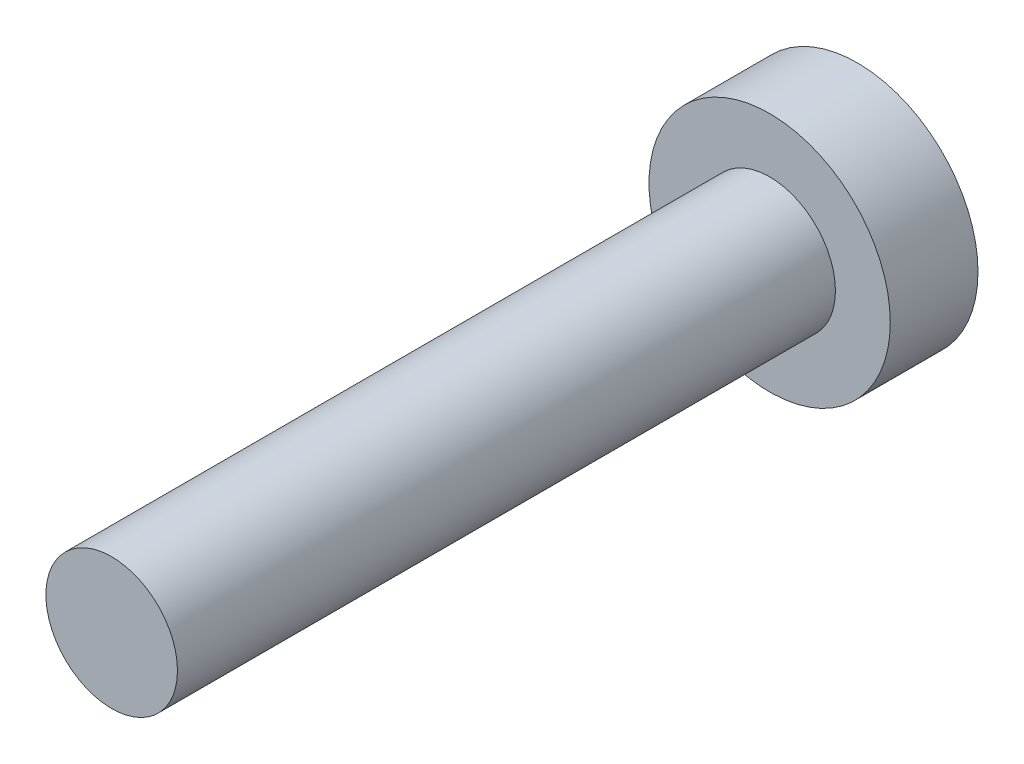
SolidWorks part; units mm, degrees
ref_plane "Plan de face" through (0, 0, 0) normal (0, 0, 1) x (1, 0, 0)
ref_plane "Plan de dessus" through (0, 0, 0) normal (0, 1, 0) x (1, 0, 0)
ref_plane "Plan de droite" through (0, 0, 0) normal (1, 0, 0) x (0, 0, -1)
sketch "Esquisse1" plane through (0, 0, 0) normal (0, 0, 1) x (1, 0, 0)
  circle A0 centre (0, 0) radius 2.75
  dimension "D1" = 5.5
extrude "Boss.-Extru.1" add sketch "Esquisse1" along normal blind 2
sketch "Esquisse2" plane through (0, 0, 2) normal (0, 0, 1) x (1, 0, 0)
  circle A0 centre (0, 0) radius 1.5
extrude "Boss.-Extru.2" add sketch "Esquisse2" along normal blind 15
